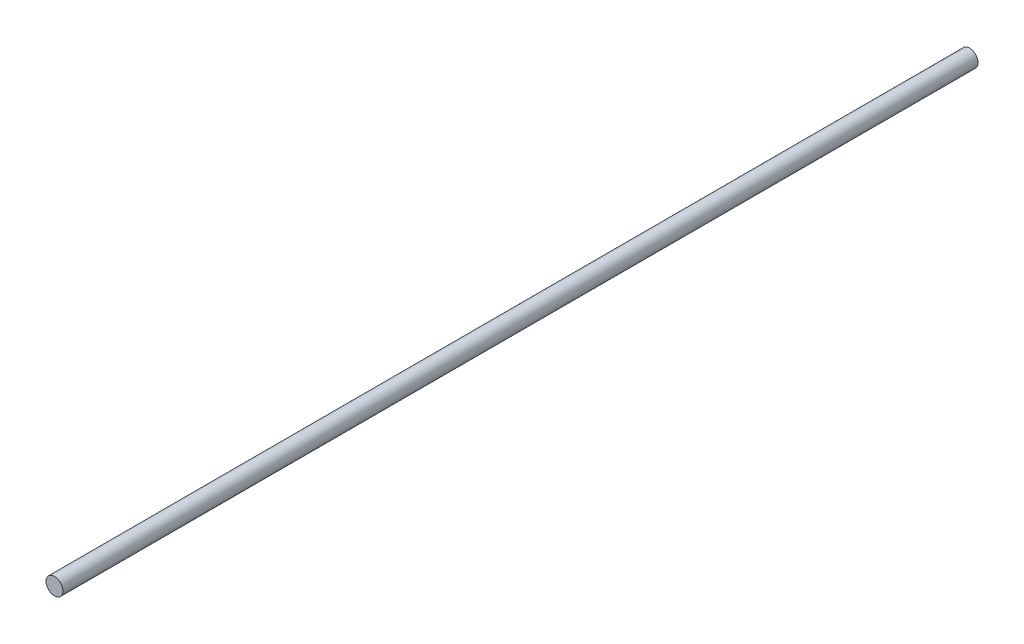
SolidWorks part; units mm, degrees
ref_plane "Front Plane" through (0, 0, 0) normal (0, 0, 1) x (1, 0, 0)
ref_plane "Top Plane" through (0, 0, 0) normal (0, 1, 0) x (1, 0, 0)
ref_plane "Right Plane" through (0, 0, 0) normal (1, 0, 0) x (0, 0, -1)
sketch "Sketch1" plane through (0, 0, 0) normal (0, 0, 1) x (1, 0, 0)
  circle A0 centre (0, 0) radius 4
  dimension "D1" = 8
extrude "Boss-Extrude1" add sketch "Sketch1" along normal blind 433
